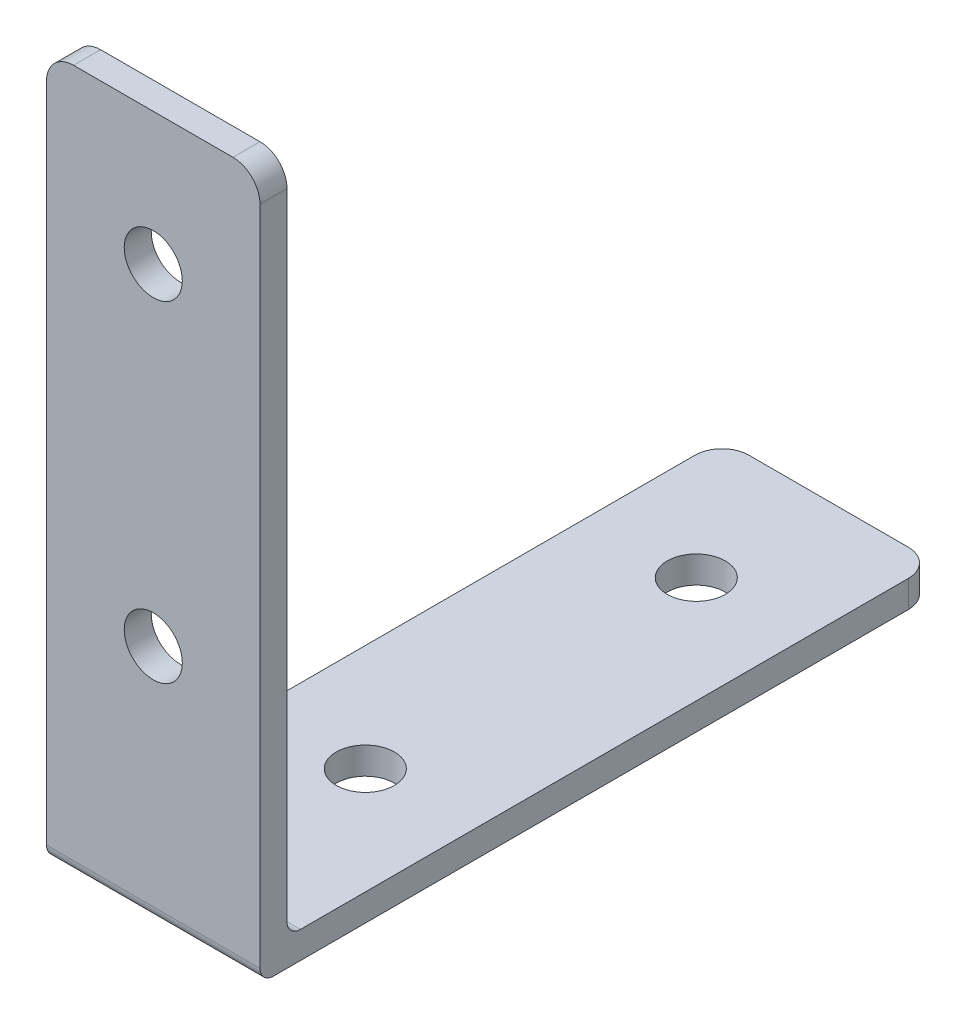
SolidWorks part; units mm, degrees
ref_plane "前基準面" through (0, 0, 0) normal (0, 0, 1) x (1, 0, 0)
ref_plane "上基準面" through (0, 0, 0) normal (0, 1, 0) x (1, 0, 0)
ref_plane "右基準面" through (0, 0, 0) normal (1, 0, 0) x (0, 0, -1)
sketch "草圖1" plane through (0, 0, 0) normal (0, 0, 1) x (1, 0, 0)
  line L1 (7.9, -1) -> (-7.9, -1)
  line L2 (7.9, -1) -> (7.9, 1)
  line L3 (7.9, 1) -> (-7.9, 1)
  line L4 (-7.9, -1) -> (-7.9, 1)
  line L5 (7.9, -1) -> (-7.9, 1) construction
  line L6 (7.9, 1) -> (-7.9, -1) construction
  point P0 (0, 0)
  dimension "D1" = 15.8
  dimension "D2" = 2
extrude "填料-伸長1" add sketch "草圖1" along normal blind 50
sketch "草圖2" plane through (0, 1, 0) normal (0, 1, 0) x (1, 0, 0)
  line L0 (7.9, -50) -> (7.9, 0) construction
  line L1 (-7.9, -50) -> (7.9, -50)
  line L2 (-7.9, -50) -> (-7.9, -48)
  line L3 (-7.9, -48) -> (7.9, -48)
  line L4 (7.9, -50) -> (7.9, -48)
  dimension "D1" = 2
extrude "填料-伸長2" add sketch "草圖2" along normal blind 50
fillet "圓角5" radius 1 1 edges at (0, -1, 50)
fillet "圓角6" radius 1 1 edges at (0, 1, 48)
fillet "圓角7" radius 2 1 edges at (7.9, 51, 49)
fillet "圓角8" radius 2 3 edges at (7.9, 0, 0) (-7.9, 0, 0) (-7.9, 51, 49)
sketch "草圖3" plane through (0, 0, 48) normal (0, 0, -1) x (-1, 0, 0)
  line L0 (0, 51) -> (0, 41.2) construction
  line L1 (-5.9, 51) -> (5.9, 51) construction
  line L2 (0, 41.2) -> (0, 16.7) construction
  circle A0 centre (0, 41.2) radius 2.15
  circle A1 centre (0, 16.7) radius 2.15
  dimension "D2" = 4.3
  dimension "D4" = 4.3
  dimension "D1" = 9.8
  dimension "D3" = 24.5
extrude "除料-伸長1" cut sketch "草圖3" against normal blind 50
sketch "草圖8" plane through (0, 1, 0) normal (0, 1, 0) x (1, 0, 0)
  line L0 (0, 0) -> (0, -9.8) construction
  line L1 (0, -9.8) -> (0, -34.3) construction
  circle A0 centre (0, -9.8) radius 2.15
  circle A1 centre (0, -34.3) radius 2.15
  dimension "D2" = 4.3
  dimension "D4" = 4.3
  dimension "D1" = 9.8
  dimension "D3" = 24.5
extrude "除料-伸長3" cut sketch "草圖8" against normal blind 50
